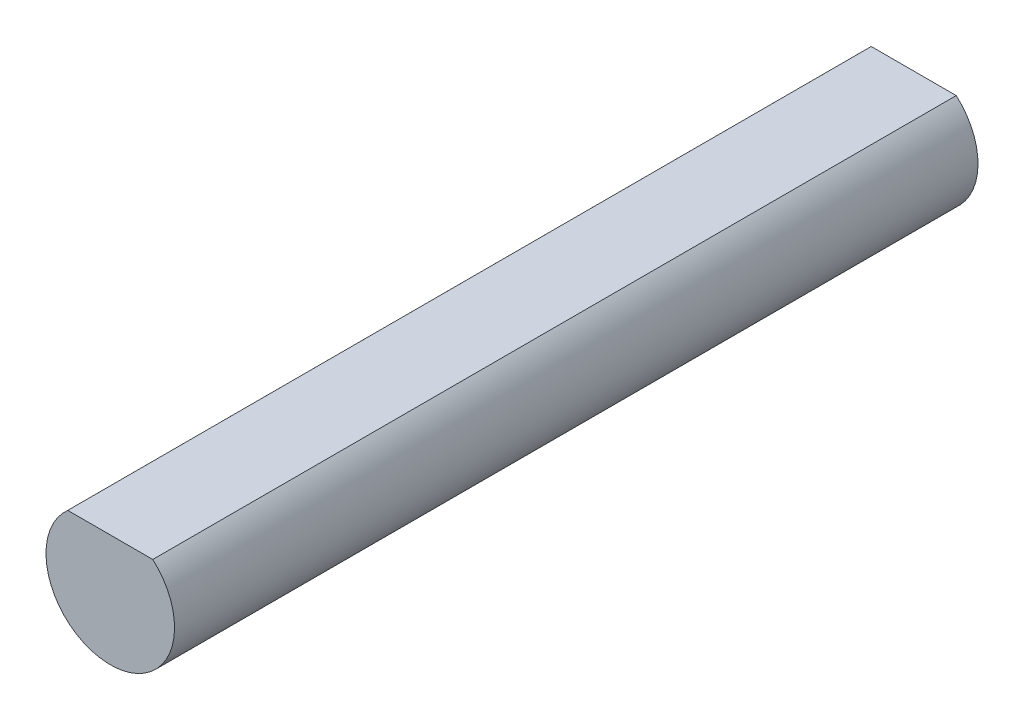
SolidWorks part; units mm, degrees
ref_plane "Front Plane" through (0, 0, 0) normal (0, 0, 1) x (1, 0, 0)
ref_plane "Top Plane" through (0, 0, 0) normal (0, 1, 0) x (1, 0, 0)
ref_plane "Right Plane" through (0, 0, 0) normal (1, 0, 0) x (0, 0, -1)
sketch "Sketch1" plane through (0, 0, 0) normal (0, 0, 1) x (1, 0, 0)
  line L0 (0, 0) -> (0, 1.5) construction
  line L1 (1.3229, 1.5) -> (-1.3229, 1.5)
  arc A0 (-1.3229, 1.5) -> (1.3229, 1.5) centre (0, 0) ccw
  dimension "D1" = 4
  dimension "D2" = 1.5
extrude "Boss-Extrude1" add sketch "Sketch1" along normal blind 25
equation "\"height\" = 25mm"
equation "\"D1@Boss-Extrude1\"=\"height\""
